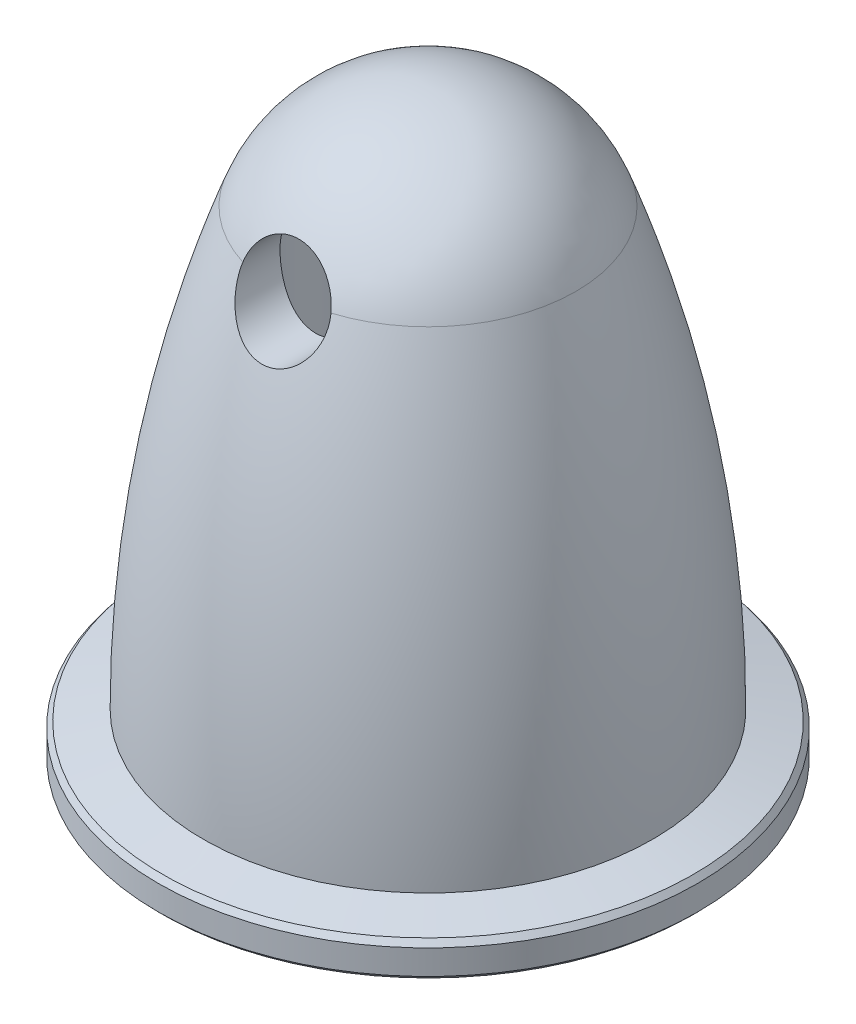
SolidWorks part; units mm, degrees
ref_plane "Front Plane" through (0, 0, 0) normal (0, 0, 1) x (1, 0, 0)
ref_plane "Top Plane" through (0, 0, 0) normal (0, 1, 0) x (1, 0, 0)
ref_plane "Right Plane" through (0, 0, 0) normal (1, 0, 0) x (0, 0, -1)
sketch "Sketch1" plane through (0, 0, 0) normal (0, 0, 1) x (1, 0, 0)
  line L0 (2.75, 0) -> (5.9, 0)
  line L1 (6, 0.1) -> (6, 0.65)
  line L2 (5.903, 0.7743) -> (5, 1)
  line L3 (2.5, 0.25) -> (2.5, 11)
  line L4 (5.9, 0) -> (6, 0.1)
  line L5 (2.5, 11) -> (0, 11.75)
  line L6 (0, 11.75) -> (0, 13)
  line L7 (6, 0.65) -> (5.903, 0.7743)
  line L8 (2.75, 0) -> (2.5, 0.25)
  arc A0 (3.2886, 10.698) -> (0, 13) centre (0, 9.5) ccw
  arc A1 (5, 1) -> (3.2886, 10.698) centre (-23.3333, 1) ccw
  point P1 (6, 0)
  point P3 (2.5, 0)
  point P4 (6, 0.75)
  dimension "D1" = 7
revolve "Revolve1" add sketch "Sketch1" angle 360 about L6
sketch "Sketch2" plane through (0, 0, 0) normal (0, 0, 1) x (1, 0, 0)
  circle A0 centre (0, 10.5) radius 1
  dimension "D1" = 10.5
extrude "Cut-Extrude1" cut sketch "Sketch2" against normal up to next and the other way up to next
